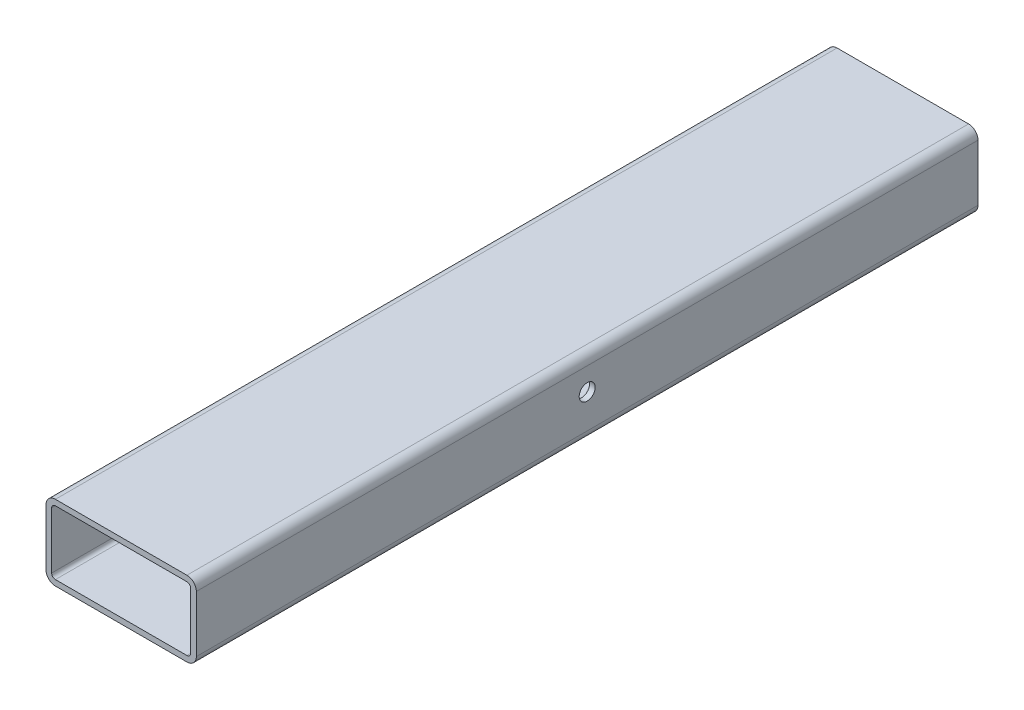
SolidWorks part; units mm, degrees
material "AISI 304"
ref_plane "Спереди" through (0, 0, 0) normal (0, 0, 1) x (1, 0, 0)
ref_plane "Сверху" through (0, 0, 0) normal (0, 1, 0) x (1, 0, 0)
ref_plane "Справа" through (0, 0, 0) normal (1, 0, 0) x (0, 0, -1)
sketch "Эскиз1" plane through (0, 0, 0) normal (0, 0, 1) x (1, 0, 0)
  line L0 (-35, -17) -> (35, -17)
  line L1 (-35, -20) -> (35, -20)
  line L2 (-40, -15) -> (-40, 15)
  line L3 (-35, 20) -> (35, 20)
  line L4 (40, -15) -> (40, 15)
  line L5 (-40, -20) -> (40, 20) construction
  line L6 (-40, 20) -> (40, -20) construction
  line L7 (37, -15) -> (37, 15)
  line L8 (-35, 17) -> (35, 17)
  line L9 (-37, -15) -> (-37, 15)
  arc A0 (35, -20) -> (40, -15) centre (35, -15) ccw
  arc A1 (35, 20) -> (40, 15) centre (35, 15) cw
  arc A2 (-40, 15) -> (-35, 20) centre (-35, 15) cw
  arc A3 (-35, -20) -> (-40, -15) centre (-35, -15) cw
  arc A4 (35, -17) -> (37, -15) centre (35, -15) ccw
  arc A5 (35, 17) -> (37, 15) centre (35, 15) cw
  arc A6 (-37, 15) -> (-35, 17) centre (-35, 15) cw
  arc A7 (-35, -17) -> (-37, -15) centre (-35, -15) cw
  point P0 (0, 0)
  dimension "D2" = 5
  dimension "D1" = 80
  dimension "D4" = 40
  dimension "D3" = 3
extrude "Бобышка-Вытянуть1" add sketch "Эскиз1" along normal mid plane 416
sketch "Эскиз2" plane through (0, 20, 0) normal (0, 1, 0) x (1, 0, 0)
  line L0 (40, -208) -> (40, 208) construction
  line L1 (-40, -208) -> (40, -208)
  line L2 (-40, -208) -> (-40, -148)
  line L3 (-40, -148) -> (40, -148)
  line L4 (40, -208) -> (40, -148)
  line L6 (-40, 208) -> (40, 208)
  line L7 (-40, 208) -> (-40, 148)
  line L8 (-40, 148) -> (40, 148)
  line L9 (40, 208) -> (40, 148)
  dimension "D1" = 60
extrude "Вырез-Вытянуть1" [suppressed] cut sketch "Эскиз2" against normal blind 5
sketch "Эскиз3" plane through (40, 0, 0) normal (1, 0, 0) x (0, 0, -1)
  line L0 (-400, 3) -> (0, 3) construction
  line L1 (0, 3) -> (400, 3) construction
  circle A1 centre (-400, 3) radius 17.8674
  circle A2 centre (0, 3) radius 17.8674
  circle A3 centre (400, 3) radius 17.8674
  dimension "D1" = 400
  dimension "D2" = 400
hole_wizard "Отверстие обработанное метчиком M101" positions "Эскиз4" profile "Эскиз5" tap size "M10" standard "DIN"
sketch "Эскиз4" plane through (40, 0, 0) normal (1, 0, 0) x (0, 0, -1)
  point P3 (400, 3)
  point P6 (0, 3)
  point P9 (-400, 3)
sketch "Эскиз5" plane through (40, 3, -400) normal (0, 1, 0) x (0, 0, -1)
  line L0 (0, 0) -> (0, 30.0537)
  line L1 (0, 30.0537) -> (4.25, 27.5)
  line L2 (4.25, 27.5) -> (4.25, 0)
  line L5 (4.25, 0) -> (0, 0)
  line L10 (0, 30.0537) -> (-4.25, 27.5) construction
  line L11 (0, -6.35) -> (0, 107.95) construction
  dimension "Диаметр сверла" = 8.5
  dimension "Глубина сверла" = 27.5
  dimension "Угол заточки сверла" = 118
cosmetic thread "Отверстие резьбы3" parameters "D1"=20, "D2"=10
